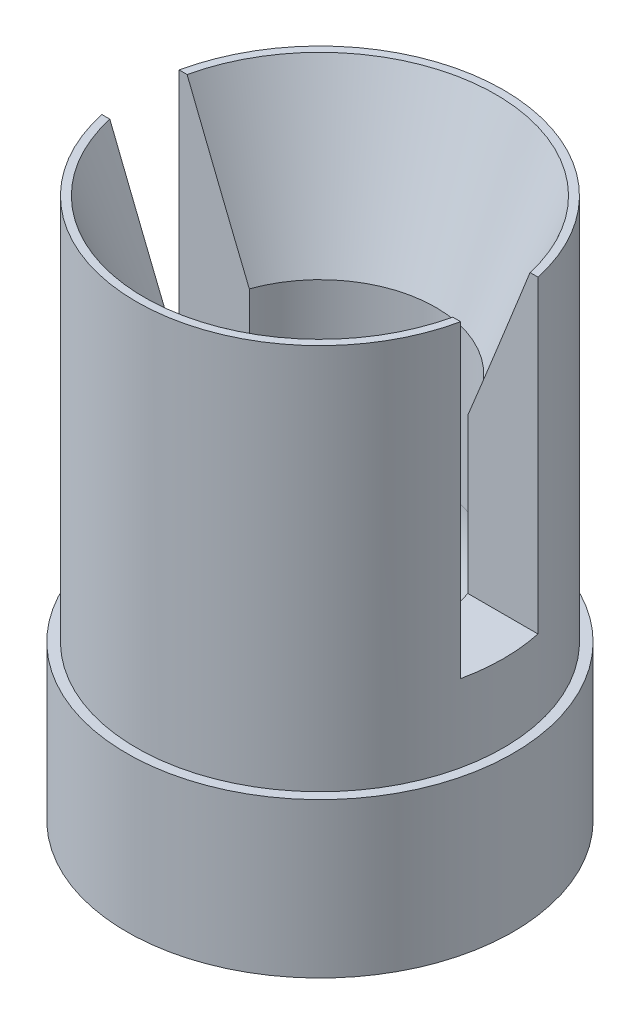
SolidWorks part; units mm, degrees
ref_plane "Plan de face" through (0, 0, 0) normal (0, 0, 1) x (1, 0, 0)
ref_plane "Plan de dessus" through (0, 0, 0) normal (0, 1, 0) x (1, 0, 0)
ref_plane "Plan de droite" through (0, 0, 0) normal (1, 0, 0) x (0, 0, -1)
sketch "Esquisse1" plane through (0, 0, 0) normal (0, 0, 1) x (1, 0, 0)
  line L0 (0, -3.5034) -> (0, 15.0866) construction
  line L1 (0, 0) -> (-5, 0)
  line L2 (-5, 0) -> (-5, 4)
  line L3 (-5, 4) -> (-4.75, 4)
  line L4 (-4.75, 4) -> (-4.75, 14)
  line L5 (-4.75, 14) -> (-4.55, 14)
  line L6 (-4.55, 14) -> (-3, 10)
  line L7 (-3, 10) -> (-3, 6)
  line L8 (0, 0) -> (0, 3)
  arc A0 (-3, 6) -> (0, 3) centre (0, 6) ccw
  dimension "D1" = 10
  dimension "D4" = 3
  dimension "D2" = 4
  dimension "D3" = 10
  dimension "D5" = 4
  dimension "D6" = 9.5
  dimension "D7" = 0.2
  dimension "D8" = 11
revolve "Révolution1" add sketch "Esquisse1" angle 360 about L0
sketch "Esquisse2" plane through (0, 0, 0) normal (1, 0, 0) x (0, 0, -1)
  line L0 (4.55, 14) -> (-4.55, 14) construction
  line L1 (-1, 6) -> (1, 6)
  line L2 (-1, 6) -> (-1, 14)
  line L3 (-1, 14) -> (1, 14)
  line L4 (1, 6) -> (1, 14)
  line L5 (-1, 6) -> (1, 14) construction
  line L6 (-1, 14) -> (1, 6) construction
  point P0 (0, 10)
  dimension "D1" = 2
  dimension "D2" = 8
extrude "Enlèv. mat.-Extru.1" cut sketch "Esquisse2" against normal up to next and the other way up to next
